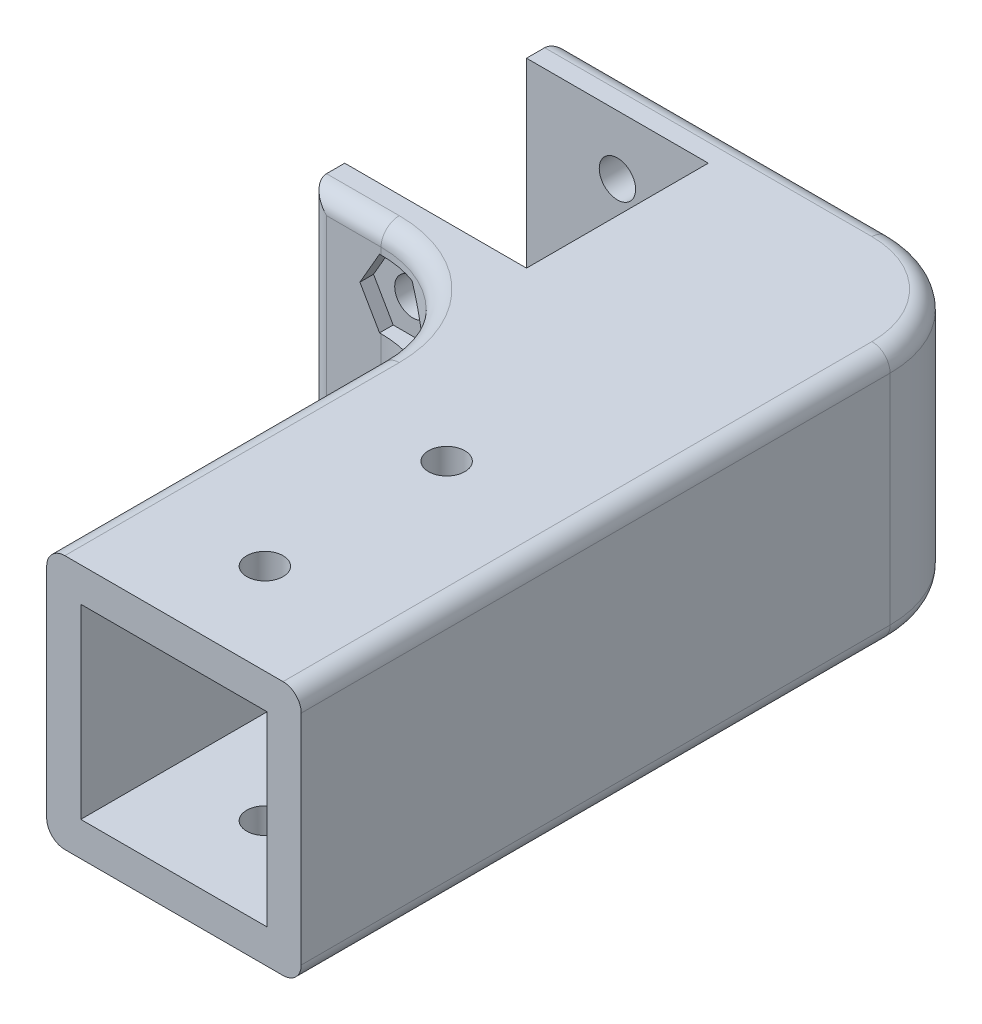
SolidWorks part; units mm, degrees
ref_plane "前视基准面" through (0, 0, 0) normal (0, 0, 1) x (1, 0, 0)
ref_plane "上视基准面" through (0, 0, 0) normal (0, 1, 0) x (1, 0, 0)
ref_plane "右视基准面" through (0, 0, 0) normal (1, 0, 0) x (0, 0, -1)
other "Configuration Table"
sketch "草图1" plane through (0, 0, 0) normal (0, 0, 1) x (1, 0, 0)
  line L1 (-10.25, 10.25) -> (10.25, 10.25)
  line L2 (-10.25, 10.25) -> (-10.25, -10.25)
  line L3 (-10.25, -10.25) -> (10.25, -10.25)
  line L4 (10.25, 10.25) -> (10.25, -10.25)
  line L5 (-10.25, 10.25) -> (10.25, -10.25) construction
  line L6 (-10.25, -10.25) -> (10.25, 10.25) construction
  line L7 (-14, -14) -> (14, -14)
  line L8 (-14, -14) -> (-14, 14)
  line L9 (-14, 14) -> (14, 14)
  line L10 (14, -14) -> (14, 14)
  line L11 (-14, -14) -> (14, 14) construction
  line L12 (-14, 14) -> (14, -14) construction
  point P0 (0, 0)
  point P5 (0, 0)
  point P11 (0, 0)
  dimension "D1" = 20.5
  dimension "D2" = 28
extrude "凸台-拉伸1" add sketch "草图1" along normal blind 50
sketch "草图2" plane through (0, 0, 0) normal (0, 0, -1) x (-1, 0, 0)
  line L4 (-14, 14) -> (-14, -14)
  line L5 (-14, -14) -> (14, -14)
  line L6 (14, -14) -> (14, 14)
  line L7 (14, 14) -> (-14, 14)
  line L8 (-14, 14) -> (-14, -14)
  line L9 (-14, -14) -> (14, -14)
  line L10 (14, -14) -> (14, 14)
  line L11 (14, 14) -> (-14, 14)
  dimension "D1" = 0
extrude "凸台-拉伸2" add sketch "草图2" against normal blind 10
sketch "草图7" plane through (14, 0, 0) normal (1, 0, 0) x (0, 0, -1)
  line L0 (-50, -14) -> (0, -14) construction
  line L1 (-1.2159, -14) -> (26.7841, -14)
  line L2 (-1.2159, -14) -> (-1.2159, 14)
  line L3 (-1.2159, 14) -> (26.7841, 14)
  line L4 (26.7841, -14) -> (26.7841, 14)
  point P4 (-1.2159, -14)
  dimension "D1" = 28
extrude "凸台-拉伸4" add sketch "草图7" against normal blind 48
sketch "草图8" plane through (-34, 0, 0) normal (-1, 0, 0) x (0, 0, 1)
  line L6 (-26.7841, 14) -> (1.2159, 14) construction
  line L7 (-22.7841, 14) -> (-2.7841, 14)
  line L8 (-22.7841, 14) -> (-22.7841, -14)
  line L9 (-22.7841, -14) -> (-2.7841, -14)
  line L10 (-2.7841, 14) -> (-2.7841, -14)
  line L11 (1.2159, -14) -> (-26.7841, -14) construction
  line L12 (1.2159, 14) -> (1.2159, -14) construction
  dimension "D1" = 20
  dimension "D2" = 4
extrude "切除-拉伸4" cut sketch "草图8" against normal blind 20
fillet "圆角4" radius 12 2 edges at (-14, 0, 1.2159) (14, 0, -26.7841)
fillet "圆角6" radius 2 14 edges at (-16, -14, -26.7841) (10.4853, -14, -23.2694) (14, 14, 17.6079) (10.4853, 14, -23.2694) (-30, 14, 1.2159) (-17.5147, 14, 4.7306) (-30, -14, 1.2159) (-17.5147, -14, 4.7306) (-34, 0, -26.7841) (-34, 0, 1.2159) (14, -14, 17.6079) (-16, 14, -26.7841) (-14, 14, 31.6079) (-14, -14, 31.6079)
sketch "草图9" plane through (0, 0, -26.7841) normal (0, 0, -1) x (-1, 0, 0)
  line L0 (24, 20.173) -> (24, -19.5863) construction
  line L1 (34, 14) -> (34, -14) construction
  line L2 (-2, 14) -> (34, 14) construction
  line L3 (34, -14) -> (-2, -14) construction
  circle A0 centre (24, 7.5) radius 2
  circle A1 centre (24, -7.5) radius 2
  dimension "D2" = 4
  dimension "D3" = 6.5
  dimension "D4" = 4
  dimension "D5" = 6.5
  dimension "D6" = 15
  dimension "D1" = 10
extrude "切除-拉伸5" cut sketch "草图9" against normal through all
sketch "草图10" plane through (0, 0, -26.7841) normal (0, 0, -1) x (-1, 0, 0)
  line L1 (19.6699, 7.5) -> (21.8349, 3.75)
  line L2 (21.8349, 3.75) -> (26.1651, 3.75)
  line L3 (26.1651, 3.75) -> (28.3301, 7.5)
  line L4 (28.3301, 7.5) -> (26.1651, 11.25)
  line L5 (26.1651, 11.25) -> (21.8349, 11.25)
  line L6 (21.8349, 11.25) -> (19.6699, 7.5)
  line L7 (19.6699, -7.5) -> (21.8349, -11.25)
  line L8 (21.8349, -11.25) -> (26.1651, -11.25)
  line L9 (26.1651, -11.25) -> (28.3301, -7.5)
  line L10 (28.3301, -7.5) -> (26.1651, -3.75)
  line L11 (26.1651, -3.75) -> (21.8349, -3.75)
  line L12 (21.8349, -3.75) -> (19.6699, -7.5)
  circle A0 centre (24, 7.5) radius 3.75 construction
  circle A1 centre (24, -7.5) radius 3.75 construction
  point P10 (0, 0)
  point P19 (0, 0)
  dimension "D1" = 7.5
  dimension "D2" = 7.5
extrude "切除-拉伸6" cut sketch "草图10" against normal through all from offset 26.5 offset against normal yes
sketch "草图12" plane through (0, 14, 0) normal (0, 1, 0) x (1, 0, 0)
  line L0 (0, 32.666) -> (0, -69.8187) construction
  line L1 (12, -50) -> (-12, -50) construction
  circle A0 centre (0, -40) radius 2
  circle A1 centre (0, -20) radius 2
  dimension "D1" = 4
  dimension "D2" = 4
  dimension "D3" = 10
  dimension "D4" = 20
extrude "切除-拉伸7" cut sketch "草图12" against normal through all
